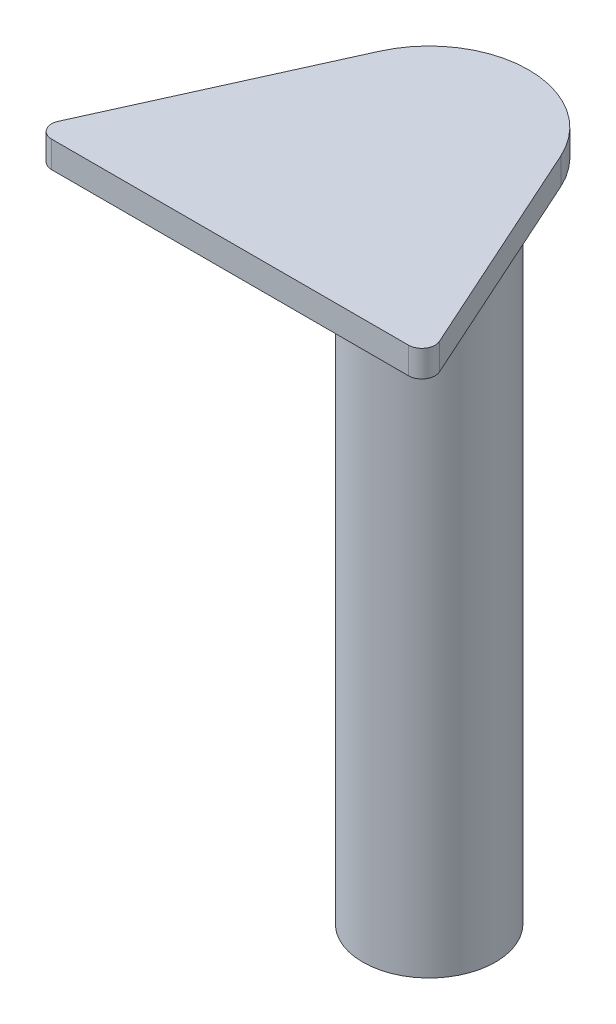
SolidWorks part; units mm, degrees
ref_plane "Front Plane" through (0, 0, 0) normal (0, 0, 1) x (1, 0, 0)
ref_plane "Top Plane" through (0, 0, 0) normal (0, 1, 0) x (1, 0, 0)
ref_plane "Right Plane" through (0, 0, 0) normal (1, 0, 0) x (0, 0, -1)
sketch "Sketch1" plane through (0, 0, 0) normal (0, 1, 0) x (1, 0, 0)
  circle A0 centre (0, 0) radius 5
  dimension "D1" = 10
extrude "Boss-Extrude1" add sketch "Sketch1" along normal blind 50
sketch "Sketch2" plane through (0, 50, 0) normal (0, 1, 0) x (1, 0, 0)
  line L0 (0, 0) -> (0, -15) construction
  line L1 (-13.4514, -15) -> (13.4514, -15)
  line L2 (-14.3629, -13.5886) -> (-6.8358, 3.0858)
  line L3 (14.3629, -13.5886) -> (6.8358, 3.0858)
  arc A0 (6.8358, 3.0858) -> (-6.8358, 3.0858) centre (0, 0) ccw
  arc A1 (13.4514, -15) -> (14.3629, -13.5886) centre (13.4514, -14) ccw
  arc A2 (-13.4514, -15) -> (-14.3629, -13.5886) centre (-13.4514, -14) cw
  point P9 (15, -15)
  point P12 (-15, -15)
  dimension "D4" = 15
  dimension "D5" = 1
  dimension "D1" = 30
  dimension "D2" = 15
  dimension "D3" = 15
extrude "Boss-Extrude2" add sketch "Sketch2" along normal blind 2
